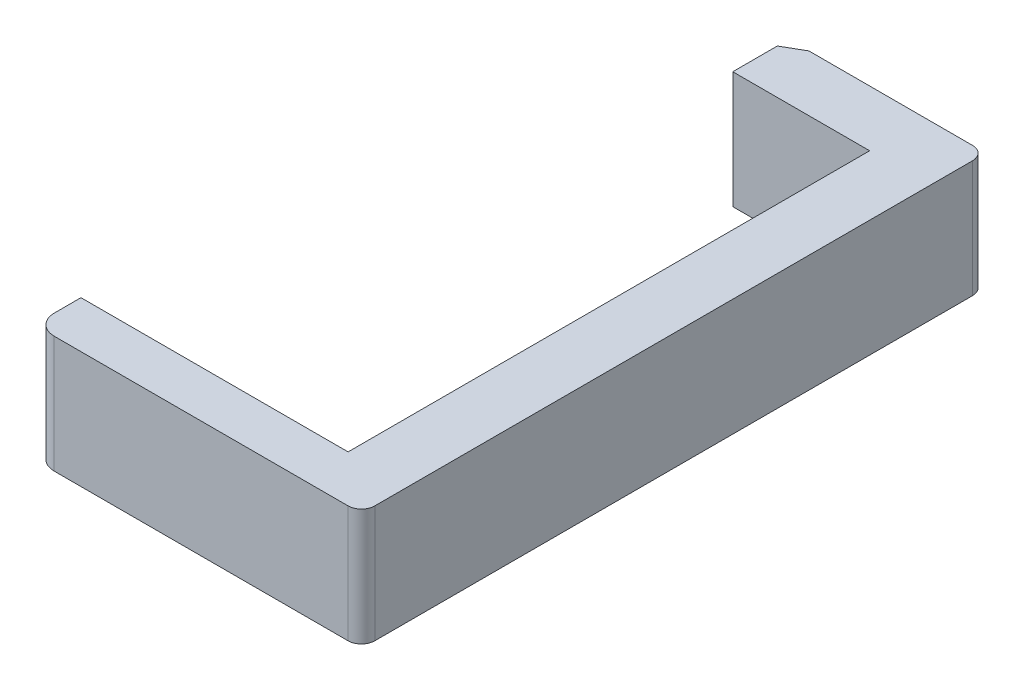
SolidWorks part; units mm, degrees
ref_plane "Front Plane" through (0, 0, 0) normal (0, 0, 1) x (1, 0, 0)
ref_plane "Top Plane" through (0, 0, 0) normal (0, 1, 0) x (1, 0, 0)
ref_plane "Right Plane" through (0, 0, 0) normal (1, 0, 0) x (0, 0, -1)
sketch "Sketch1" plane through (0, 0, 0) normal (0, 1, 0) x (1, 0, 0)
  line L0 (0, 39.05) -> (0, -39.05)
  line L1 (0, 39.05) -> (-20.5, 39.05)
  line L2 (-20.5, 39.05) -> (-20.5, 47.45)
  line L3 (-20.5, 47.45) -> (9, 47.45)
  line L4 (9, 47.45) -> (9, -46.05)
  line L5 (9, -46.05) -> (-40, -46.05)
  line L6 (-40, -46.05) -> (-40, -39.05)
  line L7 (-40, -39.05) -> (0, -39.05)
  point P8 (0, 0)
  dimension "D1" = 78.1
  dimension "D2" = 40
  dimension "D3" = 7
  dimension "D4" = 8.4
  dimension "D5" = 20.5
  dimension "D6" = 9
extrude "Boss-Extrude1" add sketch "Sketch1" along normal mid plane 17.5
fillet "Fillet1" radius 2 2 edges at (9, 0, 46.05) (9, 0, -47.45)
chamfer "Chamfer1" distance 3 angle 30 1 edges at (-20.5, 0, -47.45)
fillet "Fillet2" radius 3 1 edges at (-40, 0, 46.05)
